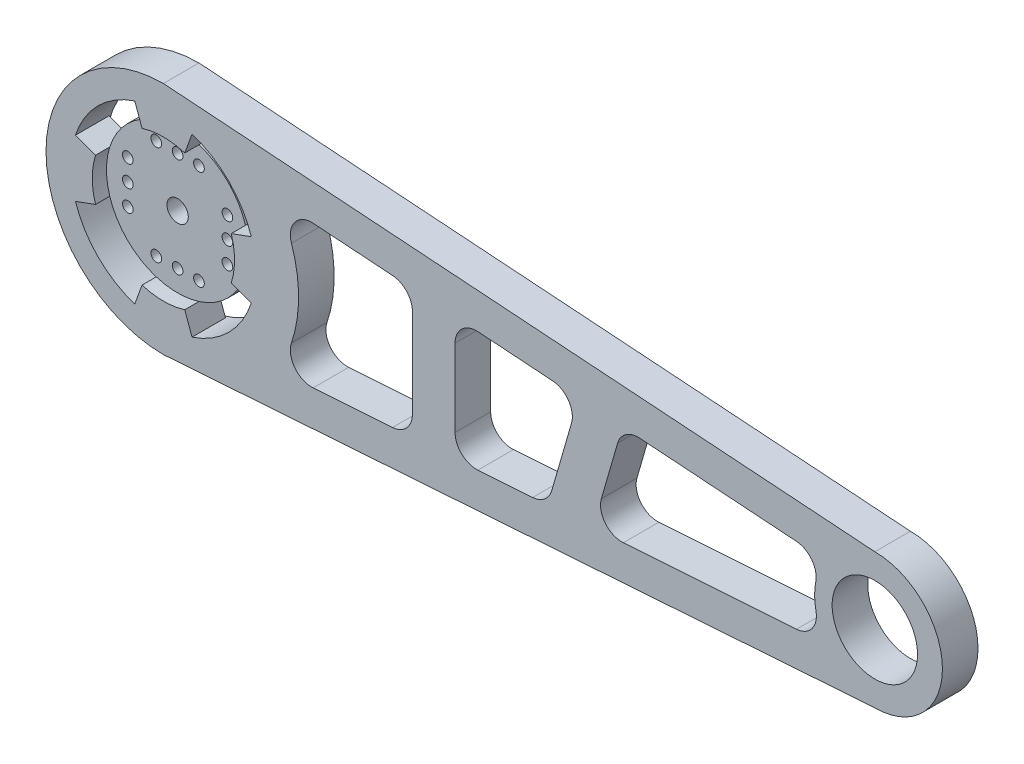
SolidWorks part; units mm, degrees
ref_plane "前视基准面" through (0, 0, 0) normal (0, 0, 1) x (1, 0, 0)
ref_plane "上视基准面" through (0, 0, 0) normal (0, 1, 0) x (1, 0, 0)
ref_plane "右视基准面" through (0, 0, 0) normal (1, 0, 0) x (0, 0, -1)
sketch "草图1" plane through (0, 0, 0) normal (0, 0, 1) x (1, 0, 0)
  line L0 (64.9709, 0) -> (-77.7905, 0) construction
  line L7 (-67.3514, 16.5) -> (32.6486, 9.5)
  line L8 (-67.3514, -16.5) -> (32.6486, -9.5)
  circle A2 centre (32.6486, 0) radius 6
  arc A4 (32.6486, -9.5) -> (32.6486, 9.5) centre (32.6486, 0) ccw
  arc A5 (-67.3514, 16.5) -> (-67.3514, -16.5) centre (-67.3514, 0) ccw
  point P3 (0, 0)
  dimension "D1" = 33
  dimension "D2" = 12
  dimension "D5" = 19
  dimension "D4" = 100
extrude "凸台-拉伸1" add sketch "草图1" along normal blind 5
sketch "草图2" plane through (0, 0, 0) normal (0, 0, -1) x (-1, 0, 0)
  line L0 (48.7055, 0) -> (85.8742, 0) construction
  line L1 (67.3514, 18.5813) -> (67.3514, -18.0319) construction
  line L2 (57.8849, 10) -> (77.3514, 10) construction
  line L3 (70.3514, 9.5394) -> (71.3783, 12.3606)
  line L4 (64.3514, 9.5394) -> (63.3246, 12.3606)
  line L5 (76.8908, 3) -> (79.712, 4.0268)
  line L6 (76.8908, -3) -> (79.712, -4.0268)
  line L7 (70.3514, -9.5394) -> (71.3783, -12.3606)
  line L8 (64.3514, -9.5394) -> (63.3246, -12.3606)
  line L9 (57.812, -3) -> (54.9908, -4.0268)
  line L10 (57.812, 3) -> (54.9908, 4.0268)
  line L11 (60.3514, -3) -> (60.3514, 4.0268) construction
  arc A0 (63.3246, 12.3606) -> (54.9908, 4.0268) centre (67.3514, 0) ccw
  arc A1 (64.3514, 9.5394) -> (57.812, 3) centre (67.3514, 0) ccw
  arc A2 (57.812, -3) -> (64.3514, -9.5394) centre (67.3514, 0) ccw
  arc A3 (54.9908, -4.0268) -> (63.3246, -12.3606) centre (67.3514, 0) ccw
  arc A4 (70.3514, -9.5394) -> (76.8908, -3) centre (67.3514, 0) ccw
  arc A5 (71.3783, -12.3606) -> (79.712, -4.0268) centre (67.3514, 0) ccw
  arc A6 (76.8908, 3) -> (70.3514, 9.5394) centre (67.3514, 0) ccw
  arc A7 (79.712, 4.0268) -> (71.3783, 12.3606) centre (67.3514, 0) ccw
  circle A12 centre (67.3514, 0) radius 1.5
  circle A13 centre (60.3514, 0) radius 0.75
  circle A14 centre (67.3514, 0) radius 10 construction
  circle A15 centre (60.3514, 3) radius 0.75
  circle A16 centre (60.3514, -3) radius 0.75
  circle A17 centre (70.3514, 7) radius 0.75
  circle A18 centre (67.3514, 7) radius 0.75
  circle A19 centre (64.3514, 7) radius 0.75
  circle A20 centre (74.3514, -3) radius 0.75
  circle A21 centre (74.3514, 0) radius 0.75
  circle A22 centre (74.3514, 3) radius 0.75
  circle A23 centre (64.3514, -7) radius 0.75
  circle A24 centre (67.3514, -7) radius 0.75
  circle A25 centre (70.3514, -7) radius 0.75
  point P30 (67.3514, 0)
  point P37 (67.3514, 0)
  point P58 (67.3514, 0)
  dimension "D1" = 26
  dimension "D2" = 20
  dimension "D4" = 110
  dimension "D6" = 1.5
  dimension "D9" = 3
  dimension "D10" = 1.5
  dimension "D7" = 7
  dimension "D8" = 1.5
  dimension "D3" = 3
  dimension "D11" = 3
  dimension "D12" = 3
  dimension "D5" = 4
  dimension "D13" = 4
extrude "切除-拉伸3" cut sketch "草图2" against normal through all
sketch "草图5" plane through (0, 0, 0) normal (0, 0, -1) x (-1, 0, 0)
  line L0 (70.3514, -9.5394) -> (71.3783, -12.3606) construction
  line L1 (63.3246, -12.3606) -> (64.3514, -9.5394) construction
  line L2 (57.812, -3) -> (54.9908, -4.0268) construction
  line L3 (54.9908, 4.0268) -> (57.812, 3) construction
  line L4 (79.712, -4.0268) -> (76.8908, -3) construction
  line L5 (76.8908, 3) -> (79.712, 4.0268) construction
  line L6 (71.3783, 12.3606) -> (70.3514, 9.5394) construction
  line L7 (64.3514, 9.5394) -> (63.3246, 12.3606) construction
  line L8 (70.3514, -9.5394) -> (71.3783, -12.3606)
  line L9 (63.3246, -12.3606) -> (64.3514, -9.5394)
  line L10 (57.812, -3) -> (54.9908, -4.0268)
  line L11 (54.9908, 4.0268) -> (57.812, 3)
  line L12 (79.712, -4.0268) -> (76.8908, -3)
  line L13 (76.8908, 3) -> (79.712, 4.0268)
  line L14 (71.3783, 12.3606) -> (70.3514, 9.5394)
  line L15 (64.3514, 9.5394) -> (63.3246, 12.3606)
  arc A0 (54.9908, 4.0268) -> (54.9908, -4.0268) centre (67.3514, 0) ccw
  arc A1 (57.812, 3) -> (57.812, -3) centre (67.3514, 0) ccw
  arc A2 (70.3514, 9.5394) -> (64.3514, 9.5394) centre (67.3514, 0) ccw
  arc A3 (71.3783, 12.3606) -> (63.3246, 12.3606) centre (67.3514, 0) ccw
  arc A4 (76.8908, -3) -> (76.8908, 3) centre (67.3514, 0) ccw
  arc A5 (79.712, -4.0268) -> (79.712, 4.0268) centre (67.3514, 0) ccw
  arc A6 (64.3514, -9.5394) -> (70.3514, -9.5394) centre (67.3514, 0) ccw
  arc A7 (63.3246, -12.3606) -> (71.3783, -12.3606) centre (67.3514, 0) ccw
extrude "切除-拉伸6" cut sketch "草图5" against normal blind 0.3
sketch "草图7" plane through (0, 0, 5) normal (0, 0, 1) x (1, 0, 0)
  line L0 (-101.7656, 0) -> (74.4294, 0) construction
  line L1 (-32.3514, 6.2404) -> (-32.3514, -6.2799)
  line L2 (-35.1419, 9.2331) -> (-46.2923, 10.0136)
  line L3 (32.6486, 9.5) -> (-67.3514, 16.5) construction
  line L7 (-35.1492, -9.2731) -> (-46.3039, -10.0269)
  line L8 (-23.1419, 8.3931) -> (-12.6586, 7.6593)
  line L9 (-23.1492, -8.4622) -> (-15.4473, -7.9417)
  line L10 (-26.3514, -5.469) -> (-26.3514, 5.4004)
  line L11 (-12.7677, -5.7822) -> (-9.9862, 3.8329)
  line L12 (-3.5059, 4.6432) -> (-5.7903, -3.2539)
  line L13 (-2.7062, -7.0807) -> (21.637, -5.4357)
  line L14 (-0.4145, 6.8022) -> (21.6093, 5.2605)
  arc A0 (-49.3487, -6.0746) -> (-49.345, 6.0635) centre (-67.3514, 0) ccw
  arc A5 (24.3457, 1.7009) -> (24.372, -1.8319) centre (33.1835, 0) ccw
  arc A6 (24.3457, 1.7009) -> (21.6093, 5.2605) centre (21.3998, 2.2678) ccw
  arc A7 (21.637, -5.4357) -> (24.372, -1.8319) centre (21.4348, -2.4425) ccw
  arc A8 (-2.7062, -7.0807) -> (-5.7903, -3.2539) centre (-2.9085, -4.0875) cw
  arc A9 (-0.4145, 6.8022) -> (-3.5059, 4.6432) centre (-0.624, 3.8095) ccw
  arc A10 (-9.9862, 3.8329) -> (-12.6586, 7.6593) centre (-12.8681, 4.6666) ccw
  arc A11 (-12.7677, -5.7822) -> (-15.4473, -7.9417) centre (-15.6495, -4.9485) cw
  arc A12 (-26.3514, -5.469) -> (-23.1492, -8.4622) centre (-23.3514, -5.469) ccw
  arc A13 (-26.3514, 5.4004) -> (-23.1419, 8.3931) centre (-23.3514, 5.4004) cw
  arc A14 (-32.3514, -6.2799) -> (-35.1492, -9.2731) centre (-35.3514, -6.2799) cw
  arc A15 (-32.3514, 6.2404) -> (-35.1419, 9.2331) centre (-35.3514, 6.2404) ccw
  arc A16 (-46.3039, -10.0269) -> (-49.3487, -6.0746) centre (-46.5061, -7.0337) cw
  arc A17 (-46.2923, 10.0136) -> (-49.345, 6.0635) centre (-46.5018, 7.021) ccw
  point P32 (-13.3514, -7.8001)
  point P35 (-26.3514, -8.6786)
  dimension "D1" = 38
  dimension "D2" = 35
  dimension "D8" = 18
  dimension "D9" = 3
  dimension "D10" = 3
  dimension "D3" = 5
  dimension "D4" = 6
  dimension "D5" = 110
  dimension "D6" = 6
  dimension "D7" = 13
extrude "切除-拉伸8" cut sketch "草图7" against normal through all
sketch "草图9" plane through (0, 0, 5) normal (0, 0, 1) x (1, 0, 0)
  circle A0 centre (-67.3514, 0) radius 10
extrude "切除-拉伸9" cut sketch "草图9" against normal blind 2
